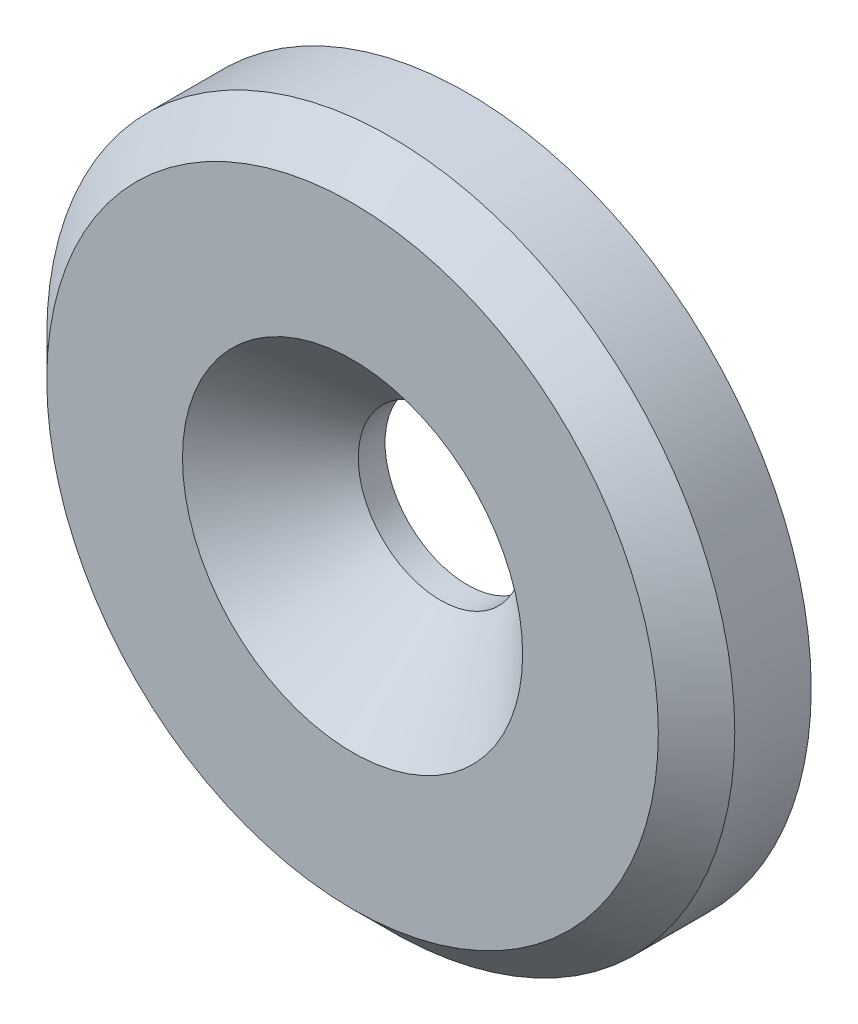
SolidWorks part; units mm, degrees
ref_plane "Спереди" through (0, 0, 0) normal (0, 0, 1) x (1, 0, 0)
ref_plane "Сверху" through (0, 0, 0) normal (0, 1, 0) x (1, 0, 0)
ref_plane "Справа" through (0, 0, 0) normal (1, 0, 0) x (0, 0, -1)
sketch "Эскиз1" plane through (0, 0, 0) normal (0, 1, 0) x (1, 0, 0)
  line L0 (9, -2) -> (9, 0)
  line L1 (9, 0) -> (2.15, 0)
  line L2 (2.15, 0) -> (2.15, -0.7)
  line L3 (2.15, -0.7) -> (4.45, -3)
  line L4 (4.45, -3) -> (8, -3)
  line L5 (8, -3) -> (9, -2)
  line L6 (0, 0.005) -> (0, -3.005) construction
revolve "Повернуть1" add sketch "Эскиз1" angle 360 about L6
